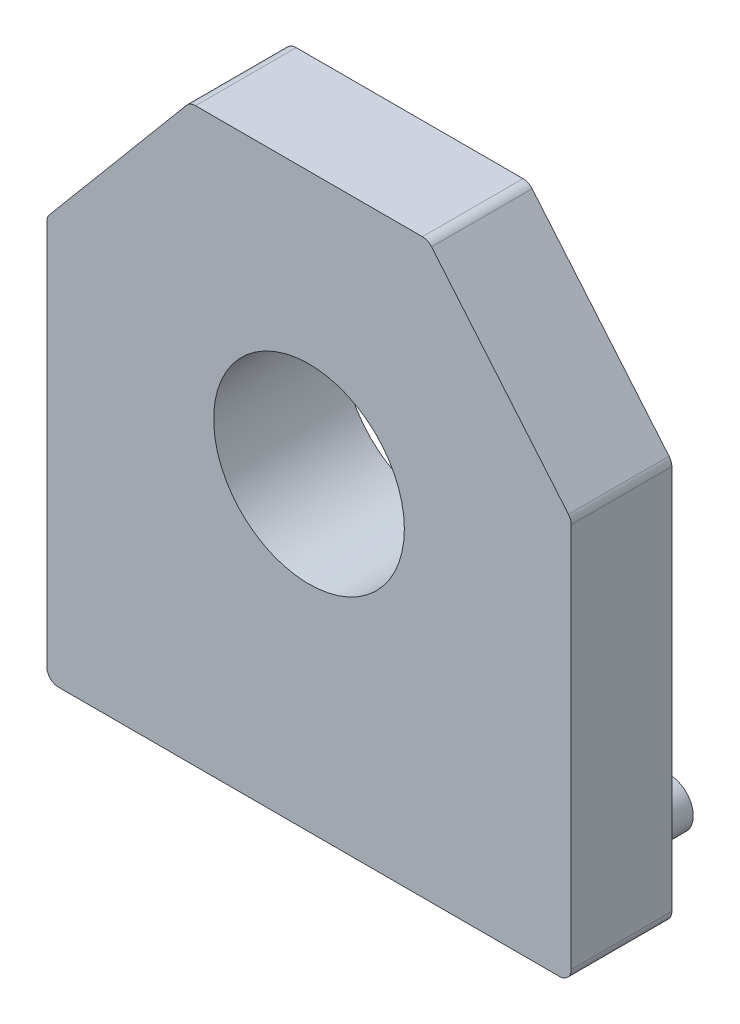
SolidWorks part; units mm, degrees
ref_plane "Plan de face" through (0, 0, 0) normal (0, 0, 1) x (1, 0, 0)
ref_plane "Plan de dessus" through (0, 0, 0) normal (0, 1, 0) x (1, 0, 0)
ref_plane "Plan de droite" through (0, 0, 0) normal (1, 0, 0) x (0, 0, -1)
sketch "Esquisse1" plane through (0, 0, 0) normal (0, 0, 1) x (1, 0, 0)
  line L0 (0, 8.42) -> (3.004, 12)
  line L1 (0, 0) -> (11, 0)
  line L2 (0, 0) -> (0, 8.42)
  line L4 (11, 0) -> (11, 8.42)
  line L5 (11, 8.42) -> (7.996, 12)
  line L6 (3.004, 12) -> (7.996, 12)
  point P1 (0, 0)
  point P9 (12.5343, 14.1941)
  point P10 (0, 0)
  dimension "D1" = 3.58
  dimension "D2" = 12
  dimension "D3" = 3.58
  dimension "D4" = 40
  dimension "D5" = 11
  dimension "D6" = 40
extrude "Extrusion1" add sketch "Esquisse1" along normal blind 2.11
fillet "Congé1" radius 0.25 6 edges at (0, 0, 1.055) (0, 8.42, 1.055) (3.004, 12, 1.055) (11, 0, 1.055) (11, 8.42, 1.055) (7.996, 12, 1.055)
sketch "Esquisse2" plane through (0, 0, 2.11) normal (0, 0, 1) x (1, 0, 0)
  line L0 (0.25, 0) -> (10.75, 0) construction
  line L1 (11, 0.25) -> (11, 8.329) construction
  circle A0 centre (5.5, 6.5) radius 2
  dimension "D1" = 4
  dimension "D2" = 6.5
  dimension "D3" = 5.5
extrude "Extrusion2" cut sketch "Esquisse2" against normal through all
sketch "Esquisse3" plane through (0, 0, 0) normal (0, 0, -1) x (-1, 0, 0)
  circle A0 centre (-5.5, 6.5) radius 2.5
  circle A1 centre (-5.5, 6.5) radius 2
  dimension "D1" = 5
extrude "Extrusion3" add sketch "Esquisse3" along normal blind 0.6
sketch "Esquisse4" plane through (0, 0, 0) normal (0, 0, -1) x (-1, 0, 0)
  line L0 (-12.3768, 1.01) -> (2.5545, 1.01) construction
  line L1 (-11, 0.25) -> (-11, 8.329) construction
  circle A0 centre (-5.5, 6.5) radius 2 construction
  circle A1 centre (-9.75, 1.01) radius 0.5
  circle A2 centre (-1.25, 1.01) radius 0.5
  dimension "D2" = 1
  dimension "D3" = 1
  dimension "D1" = 5.49
  dimension "D4" = 8.5
  dimension "D5" = 1.25
extrude "Extrusion4" add sketch "Esquisse4" along normal blind 1.2
